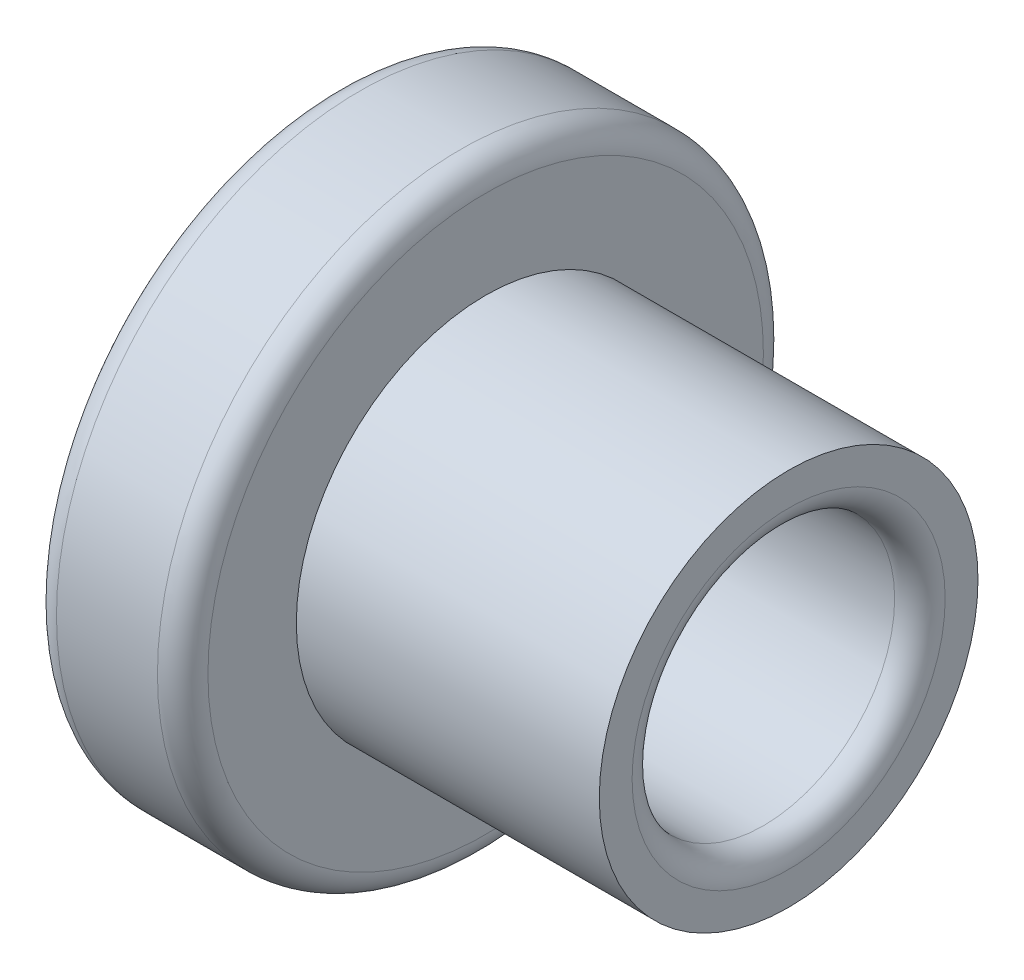
SolidWorks part; units mm, degrees
ref_plane "Front Plane" through (0, 0, 0) normal (0, 0, 1) x (1, 0, 0)
ref_plane "Top Plane" through (0, 0, 0) normal (0, 1, 0) x (1, 0, 0)
ref_plane "Right Plane" through (0, 0, 0) normal (1, 0, 0) x (0, 0, -1)
sketch "Sketch1" plane through (0, 0, 0) normal (1, 0, 0) x (0, 0, -1)
  circle A0 centre (0, 0) radius 7.62
  circle A1 centre (0, 0) radius 3.302
  dimension "D1" = 6.604
  dimension "D2" = 15.24
extrude "Boss-Extrude1" add sketch "Sketch1" along normal blind 3.81
sketch "Sketch2" plane through (3.81, 0, 0) normal (1, 0, 0) x (0, 0, -1)
  circle A0 centre (0, 0) radius 3.302
  circle A1 centre (0, 0) radius 4.7625
  circle A2 centre (0, 0) radius 3.302 construction
  dimension "D1" = 9.525
extrude "Boss-Extrude2" add sketch "Sketch2" along normal blind 10.795 contours A1 | A0
fillet "Fillet1" radius 0.635 3 edges at (0, 0, -7.62) (3.81, 0, -7.62) (14.605, 0, -3.302)
chamfer "Chamfer1" distance 3.175 angle 49 1 edges at (0, 0, -3.302)
sketch "Sketch3" plane through (14.605, 0, 0) normal (1, 0, 0) x (0, 0, -1)
  circle A0 centre (0, 0) radius 4.7625
  circle A1 centre (0, 0) radius 4.7625 construction
extrude "Cut-Extrude1" cut sketch "Sketch3" against normal offset from surface (3.175 mm away) 7.62 up to face at (3.81, 0, -6.985)
fillet "Fillet2" radius 0.635 1 edges at (11.43, 0, -3.302)
